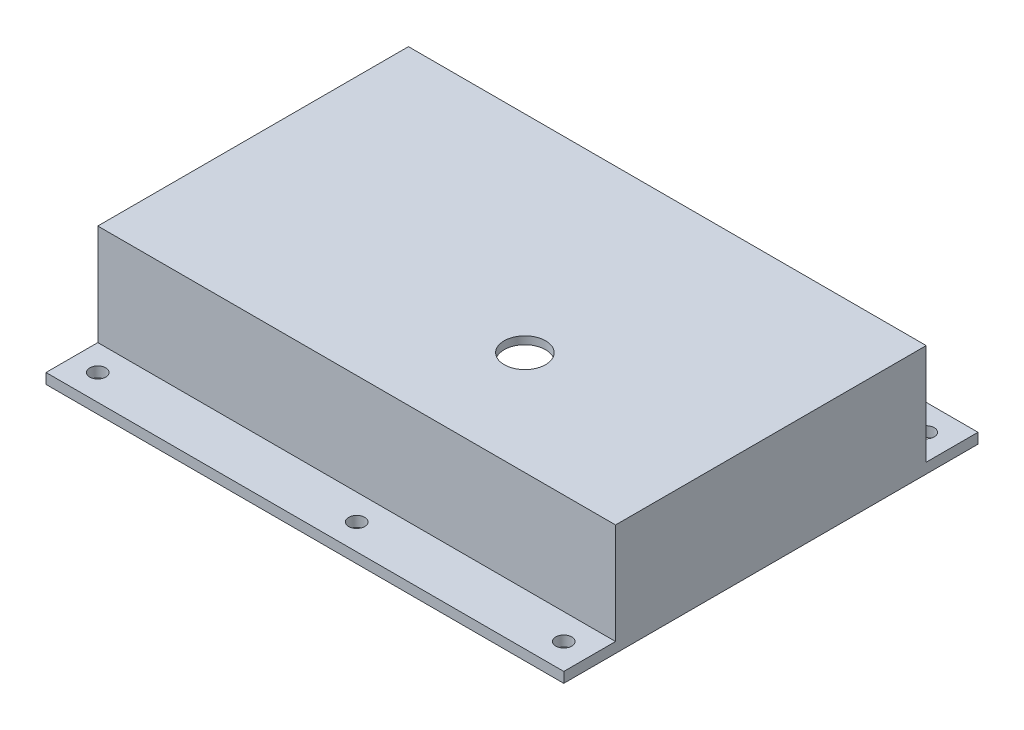
SolidWorks part; units mm, degrees
ref_plane "Płaszczyzna przednia" through (0, 0, 0) normal (0, 0, 1) x (1, 0, 0)
ref_plane "Płaszczyzna górna" through (0, 0, 0) normal (0, 1, 0) x (1, 0, 0)
ref_plane "Płaszczyzna prawa" through (0, 0, 0) normal (1, 0, 0) x (0, 0, -1)
sketch "Sketch1" plane through (0, 0, 0) normal (0, 1, 0) x (1, 0, 0)
  line L1 (-50, -40) -> (50, -40)
  line L2 (-50, -40) -> (-50, 40)
  line L3 (-50, 40) -> (50, 40)
  line L4 (50, -40) -> (50, 40)
  line L5 (-50, -40) -> (50, 40) construction
  line L6 (-50, 40) -> (50, -40) construction
  line L7 (-50, -30) -> (50, -30)
  line L8 (-50, -30) -> (-50, 30)
  line L9 (-50, 30) -> (50, 30)
  line L10 (50, -30) -> (50, 30)
  line L11 (-50, -30) -> (50, 30) construction
  line L12 (-50, 30) -> (50, -30) construction
  line L13 (-48.5, -28.5) -> (48.5, -28.5)
  line L14 (-48.5, -28.5) -> (-48.5, 28.5)
  line L15 (-48.5, 28.5) -> (48.5, 28.5)
  line L16 (48.5, -28.5) -> (48.5, 28.5)
  line L17 (-48.5, -28.5) -> (48.5, 28.5) construction
  line L18 (-48.5, 28.5) -> (48.5, -28.5) construction
  point P0 (0, 0)
  point P6 (0, 0)
  point P11 (0, 0)
  dimension "D1" = 100
  dimension "D2" = 80
  dimension "D3" = 100
  dimension "D4" = 60
  dimension "D5" = 97
  dimension "D6" = 57
extrude "Boss-Extrude1" add sketch "Sketch1" along normal blind 20 contours L9 L2 L7 L4 L16 L13 L14 L15
sketch "Sketch2" plane through (0, 20, 0) normal (0, 1, 0) x (1, 0, 0)
  line L1 (-50, 30) -> (50, 30)
  line L2 (-50, 30) -> (-50, -30)
  line L3 (-50, -30) -> (50, -30)
  line L4 (50, 30) -> (50, -30)
extrude "Boss-Extrude2" add sketch "Sketch2" along normal blind 1.5
sketch "Sketch3" plane through (50, 0, 0) normal (1, 0, 0) x (0, 0, -1)
  line L1 (-30, 0) -> (-40, 0)
  line L2 (-30, 0) -> (-30, 2)
  line L3 (-30, 2) -> (-40, 2)
  line L4 (-40, 0) -> (-40, 2)
  line L5 (30, 0) -> (40, 0)
  line L6 (30, 0) -> (30, 2)
  line L7 (30, 2) -> (40, 2)
  line L8 (40, 0) -> (40, 2)
  dimension "D1" = 10
  dimension "D2" = 2
  dimension "D3" = 2
  dimension "D4" = 10
extrude "Boss-Extrude3" add sketch "Sketch3" against normal blind 100
sketch "Sketch4" plane through (0, 0, 0) normal (0, -1, 0) x (1, 0, 0)
  line L0 (-45, 35) -> (5, 35) construction
  line L5 (-45, -35) -> (45, 35) construction
  line L6 (-45, 35) -> (45, -35) construction
  line L7 (-45, -35) -> (5, -35) construction
  circle A0 centre (-45, 35) radius 1.55
  circle A1 centre (45, 35) radius 1.55
  circle A2 centre (45, -35) radius 1.55
  circle A3 centre (-45, -35) radius 1.55
  circle A4 centre (5, 35) radius 1.55
  circle A5 centre (5, -35) radius 1.55
  point P0 (0, 0)
  dimension "D1" = 90
  dimension "D2" = 70
extrude "Cut-Extrude1" cut sketch "Sketch4" against normal blind 2
sketch "Sketch5" plane through (0, 21.5, 0) normal (0, 1, 0) x (1, 0, 0)
  circle A0 centre (12.44, -9.95) radius 4
extrude "Cut-Extrude2" cut sketch "Sketch5" against normal blind 3
